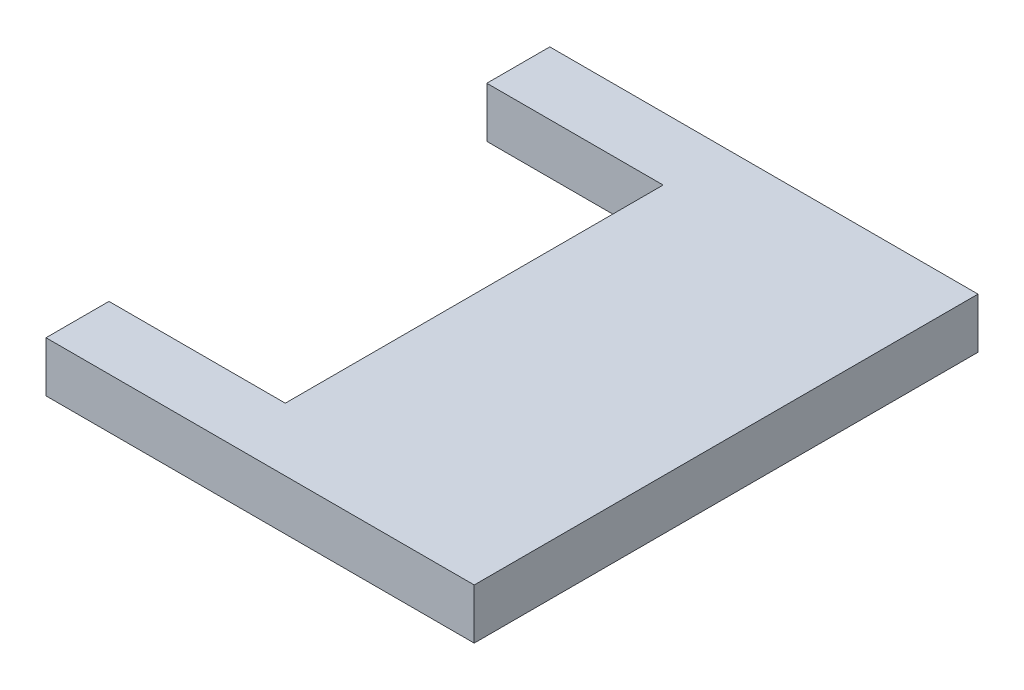
SolidWorks part; units mm, degrees
ref_plane "Front Plane" through (0, 0, 0) normal (0, 0, 1) x (1, 0, 0)
ref_plane "Top Plane" through (0, 0, 0) normal (0, 1, 0) x (1, 0, 0)
ref_plane "Right Plane" through (0, 0, 0) normal (1, 0, 0) x (0, 0, -1)
sketch "Sketch1" plane through (0, 0, 0) normal (0, 1, 0) x (1, 0, 0)
  line L0 (-2, 13.2967) -> (-2, -16.3004) construction
  line L1 (-4, 10) -> (15, 10)
  line L3 (-4, -10) -> (15, -10)
  line L4 (15, 10) -> (15, -10)
  line L5 (-4, 2.6667) -> (15, -10) construction
  line L6 (-4, -2.6667) -> (15, 10) construction
  line L7 (-2, 7.5) -> (-2, 2.5)
  line L8 (-2, 7.5) -> (0, 7.5)
  line L9 (-2, 2.5) -> (0, 2.5)
  line L10 (0, 7.5) -> (0, 2.5)
  line L11 (-2, -2.5) -> (-2, -7.5)
  line L12 (-2, -2.5) -> (0, -2.5)
  line L13 (-2, -7.5) -> (0, -7.5)
  line L14 (0, -2.5) -> (0, -7.5)
  line L15 (-4, 10) -> (-4, -10)
  point P0 (0, 0)
  point P8 (0, 5)
  point P15 (0, -5)
  dimension "D1" = 2
  dimension "D3" = 17
  dimension "D4" = 2
  dimension "D5" = 2
  dimension "D6" = 5
  dimension "D7" = 5
  dimension "D8" = 5
  dimension "D9" = 5
extrude "Boss-Extrude1" add sketch "Sketch1" along normal blind 2
sketch "Sketch2" plane through (0, 2, 0) normal (0, 1, 0) x (1, 0, 0)
  line L0 (0, 7.5) -> (0, -7.5)
  line L1 (0, -7.5) -> (5, -7.5)
  line L2 (5, -7.5) -> (5, 7.5)
  line L3 (5, 7.5) -> (0, 7.5)
  dimension "D1" = 5
extrude "Cut-Extrude1" cut sketch "Sketch2" against normal blind 10
sketch "Sketch3" plane through (0, 2, 0) normal (0, 1, 0) x (1, 0, 0)
  line L0 (-4, -10) -> (15, -10) construction
  line L1 (-4, 10) -> (-2, 10)
  line L2 (-4, 10) -> (-4, -10)
  line L3 (-4, -10) -> (-2, -10)
  line L4 (-2, 10) -> (-2, 3.8924)
  line L5 (-2, 3.8924) -> (1.5395, 3.8924)
  line L6 (1.5395, 3.8924) -> (1.5395, -3.1899)
  line L7 (1.5395, -3.1899) -> (-2, -3.1899)
  line L8 (-2, -3.1899) -> (-2, -10)
  dimension "D1" = 2
extrude "Cut-Extrude3" cut sketch "Sketch3" against normal blind 10
